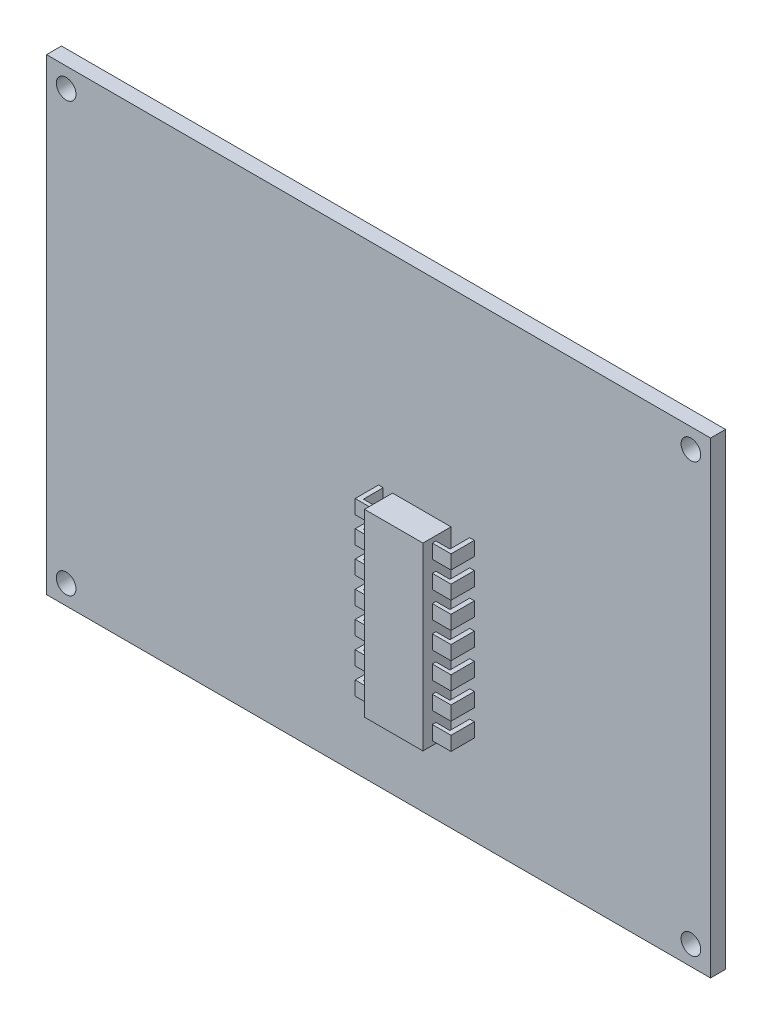
SolidWorks part; units mm, degrees
ref_plane "Спереди" through (0, 0, 0) normal (0, 0, 1) x (1, 0, 0)
ref_plane "Сверху" through (0, 0, 0) normal (0, 1, 0) x (1, 0, 0)
ref_plane "Справа" through (0, 0, 0) normal (1, 0, 0) x (0, 0, -1)
sketch "Эскиз1" plane through (0, 0, 0) normal (0, 0, 1) x (1, 0, 0)
  line L0 (35.5, 50) -> (35.5, 35.7681) construction
  line L1 (0, 0) -> (71, 0)
  line L2 (0, 0) -> (0, 50)
  line L3 (0, 50) -> (71, 50)
  line L4 (71, 0) -> (71, 50)
  line L5 (0, 25) -> (29.8666, 25) construction
  circle A0 centre (2.1, 47.9) radius 1.05
  circle A1 centre (68.9, 47.9) radius 1.05
  circle A2 centre (68.9, 2.1) radius 1.05
  circle A3 centre (2.1, 2.1) radius 1.05
  dimension "D3" = 2.1
  dimension "D1" = 71
  dimension "D2" = 50
  dimension "D4" = 2.1
  dimension "D5" = 2.1
extrude "Бобышка-Вытянуть1" add sketch "Эскиз1" along normal blind 1.6
sketch "Эскиз2" plane through (0, 0, 1.6) normal (0, 0, 1) x (1, 0, 0)
  line L0 (71, 50) -> (0, 50) construction
  line L1 (37.5, 28.4) -> (43.75, 28.4)
  line L2 (37.5, 28.4) -> (37.5, 9.15)
  line L3 (37.5, 9.15) -> (43.75, 9.15)
  line L4 (43.75, 28.4) -> (43.75, 9.15)
  line L5 (0, 50) -> (0, 0) construction
  dimension "D1" = 21.6
  dimension "D2" = 37.5
  dimension "D3" = 19.25
  dimension "D4" = 6.25
extrude "Бобышка-Вытянуть2" add sketch "Эскиз2" along normal blind 3.5
sketch "Эскиз4" plane through (0, 0, 5.1) normal (0, 0, 1) x (1, 0, 0)
  line L0 (37.5, 28.4) -> (37.5, 9.15) construction
  line L1 (37.5, 27.9) -> (35.5, 27.9)
  line L2 (37.5, 27.9) -> (37.5, 26.4)
  line L3 (37.5, 26.4) -> (35.5, 26.4)
  line L4 (35.5, 27.9) -> (35.5, 26.4)
  line L5 (45.75, 27.9) -> (43.75, 27.9)
  line L6 (45.75, 27.9) -> (45.75, 26.4)
  line L7 (45.75, 26.4) -> (43.75, 26.4)
  line L8 (43.75, 27.9) -> (43.75, 26.4)
  line L9 (45.75, 25.1) -> (43.75, 25.1)
  line L10 (45.75, 25.1) -> (45.75, 23.6)
  line L11 (45.75, 23.6) -> (43.75, 23.6)
  line L12 (43.75, 25.1) -> (43.75, 23.6)
  line L13 (45.75, 22.3) -> (43.75, 22.3)
  line L14 (45.75, 22.3) -> (45.75, 20.8)
  line L15 (45.75, 20.8) -> (43.75, 20.8)
  line L16 (43.75, 22.3) -> (43.75, 20.8)
  line L17 (45.75, 19.5) -> (43.75, 19.5)
  line L18 (45.75, 19.5) -> (45.75, 18)
  line L19 (45.75, 18) -> (43.75, 18)
  line L20 (43.75, 19.5) -> (43.75, 18)
  line L21 (45.75, 16.7) -> (43.75, 16.7)
  line L22 (45.75, 16.7) -> (45.75, 15.2)
  line L23 (45.75, 15.2) -> (43.75, 15.2)
  line L24 (43.75, 16.7) -> (43.75, 15.2)
  line L25 (45.75, 13.9) -> (43.75, 13.9)
  line L26 (45.75, 13.9) -> (45.75, 12.4)
  line L27 (45.75, 12.4) -> (43.75, 12.4)
  line L28 (43.75, 13.9) -> (43.75, 12.4)
  line L29 (45.75, 11.1) -> (43.75, 11.1)
  line L30 (45.75, 11.1) -> (45.75, 9.6)
  line L31 (45.75, 9.6) -> (43.75, 9.6)
  line L32 (43.75, 11.1) -> (43.75, 9.6)
  line L33 (37.5, 25.1) -> (35.5, 25.1)
  line L34 (37.5, 25.1) -> (37.5, 23.6)
  line L35 (37.5, 23.6) -> (35.5, 23.6)
  line L36 (35.5, 25.1) -> (35.5, 23.6)
  line L37 (37.5, 22.3) -> (35.5, 22.3)
  line L38 (37.5, 22.3) -> (37.5, 20.8)
  line L39 (37.5, 20.8) -> (35.5, 20.8)
  line L40 (35.5, 22.3) -> (35.5, 20.8)
  line L41 (37.5, 19.5) -> (35.5, 19.5)
  line L42 (37.5, 19.5) -> (37.5, 18)
  line L43 (37.5, 18) -> (35.5, 18)
  line L44 (35.5, 19.5) -> (35.5, 18)
  line L45 (37.5, 16.7) -> (35.5, 16.7)
  line L46 (37.5, 16.7) -> (37.5, 15.2)
  line L47 (37.5, 15.2) -> (35.5, 15.2)
  line L48 (35.5, 16.7) -> (35.5, 15.2)
  line L49 (37.5, 13.9) -> (35.5, 13.9)
  line L50 (37.5, 13.9) -> (37.5, 12.4)
  line L51 (37.5, 12.4) -> (35.5, 12.4)
  line L52 (35.5, 13.9) -> (35.5, 12.4)
  line L53 (37.5, 11.1) -> (35.5, 11.1)
  line L54 (37.5, 11.1) -> (37.5, 9.6)
  line L55 (37.5, 9.6) -> (35.5, 9.6)
  line L56 (35.5, 11.1) -> (35.5, 9.6)
  dimension "D1" = 1.5
  dimension "D2" = 2
  dimension "D3" = 0.5
  dimension "D6" = 6.25
  dimension "D4" = 2
  dimension "D5" = 7
extrude "Бобышка-Вытянуть3" add sketch "Эскиз4" against normal up to surface (2.5 mm away) from offset 1 up to face at (1.05, 2.1, 1.6) offset against normal yes
sketch "Эскиз5" plane through (0, 9.15, 0) normal (0, -1, 0) x (1, 0, 0)
  line L0 (40.625, 5.1) -> (40.625, 1.6) construction
  line L1 (35.5, 1.6) -> (37.5, 1.6) construction
  line L3 (35.5, 1.6) -> (35.5, 4.1) construction
  line L5 (36, 1.6) -> (36, 3.7161)
  line L6 (36, 3.7161) -> (37.5, 3.7161)
  line L7 (37.5, 1.6) -> (37.5, 4.1) construction
  line L8 (37.5, 3.7161) -> (37.5, 2.1)
  line L9 (37.5, 5.1) -> (43.75, 5.1) construction
  line L10 (37.5, 1.6) -> (43.75, 1.6) construction
  line L11 (36, 1.6) -> (45.25, 1.6)
  line L12 (37.5, 2.1) -> (43.75, 2.1)
  line L13 (43.75, 3.7161) -> (43.75, 2.1)
  line L14 (45.25, 3.7161) -> (43.75, 3.7161)
  line L15 (45.25, 1.6) -> (45.25, 3.7161)
  point P18 (40.625, 2.1)
  dimension "D1" = 0.5
  dimension "D2" = 0.5
extrude "Вырез-Вытянуть1" cut sketch "Эскиз5" against normal through all both and the other way through all
